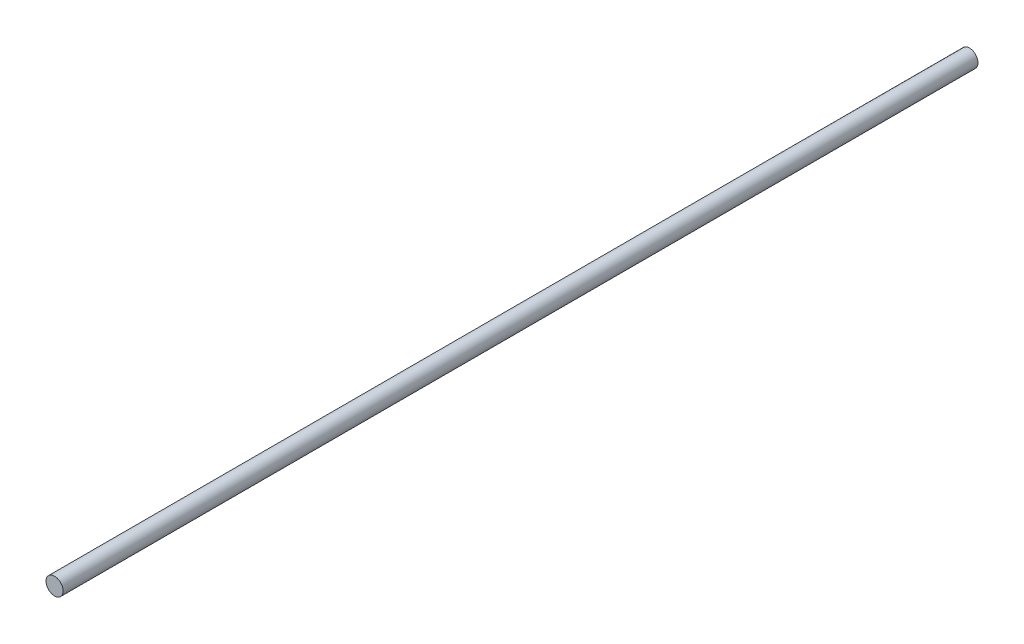
SolidWorks part; units mm, degrees
material "AISI 304"
ref_plane "Front Plane" through (0, 0, 0) normal (0, 0, 1) x (1, 0, 0)
ref_plane "Top Plane" through (0, 0, 0) normal (0, 1, 0) x (1, 0, 0)
ref_plane "Right Plane" through (0, 0, 0) normal (1, 0, 0) x (0, 0, -1)
sketch "Sketch1" plane through (0, 0, 0) normal (0, 0, 1) x (1, 0, 0)
  circle A0 centre (0, 0) radius 1.5
  dimension "D1" = 3
extrude "Boss-Extrude1" add sketch "Sketch1" along normal blind 160 contours A0
